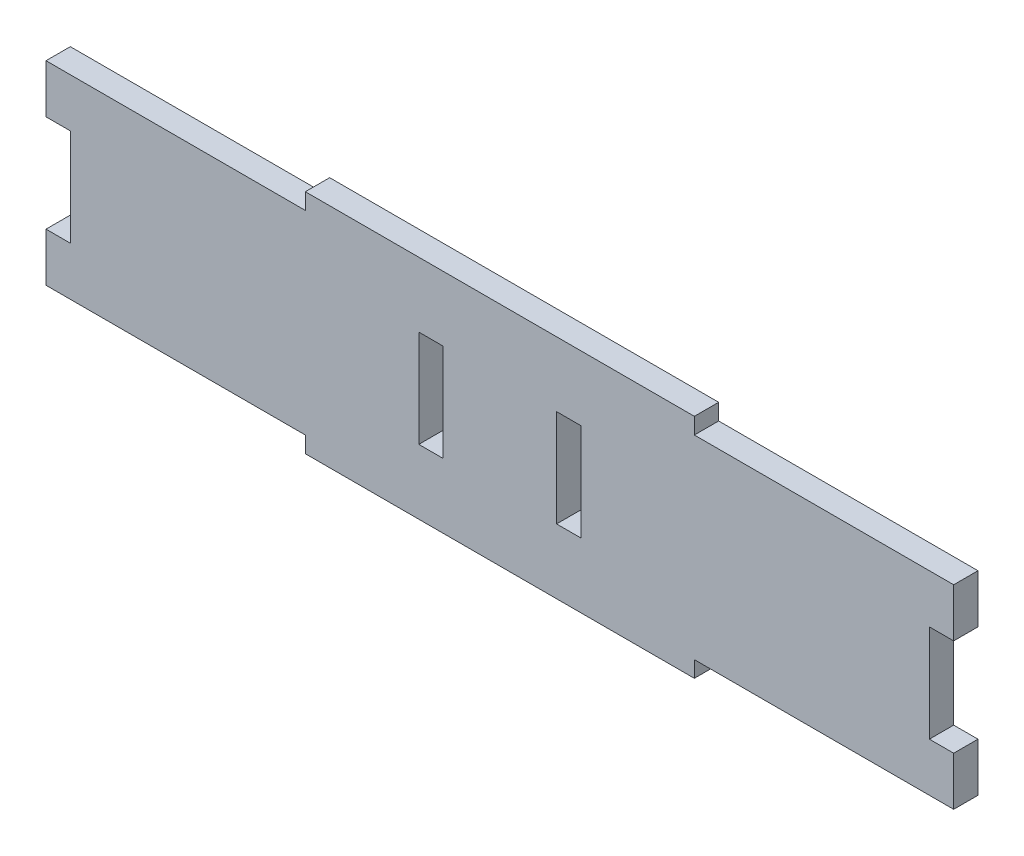
SolidWorks part; units mm, degrees
material "2024 Alloy"
ref_plane "Front" through (0, 0, 0) normal (0, 0, 1) x (1, 0, 0)
ref_plane "Top" through (0, 0, 0) normal (0, 1, 0) x (1, 0, 0)
ref_plane "Right" through (0, 0, 0) normal (1, 0, 0) x (0, 0, -1)
sketch "Sketch1" plane through (0, 0, 0) normal (0, 0, 1) x (1, 0, 0)
  line L0 (-177.8, 0) -> (177.8, 0) construction
  line L1 (-177.8, -44.45) -> (177.8, -44.45)
  line L2 (-177.8, -44.45) -> (-177.8, 44.45)
  line L4 (177.8, -44.45) -> (177.8, 44.45)
  line L5 (-177.8, -44.45) -> (177.8, 44.45) construction
  line L6 (-177.8, 44.45) -> (177.8, -44.45) construction
  line L11 (0, 44.45) -> (0, -44.45) construction
  line L16 (152.4, 50.8) -> (130.175, 50.8)
  line L17 (-177.8, 44.45) -> (177.8, 44.45)
  line L18 (-76.2, -44.45) -> (-76.2, -38.1)
  line L19 (76.2, 38.1) -> (76.2, 44.45)
  line L20 (76.2, -38.1) -> (76.2, -44.45)
  line L27 (-177.8, 19.05) -> (-177.8, -19.05)
  line L28 (177.8, 19.05) -> (177.8, -19.05)
  line L29 (-76.2, -38.1) -> (-177.8, -38.1)
  line L30 (76.2, -38.1) -> (177.8, -38.1)
  line L31 (76.2, 38.1) -> (177.8, 38.1)
  line L32 (-76.2, 44.45) -> (-76.2, 38.1)
  line L33 (-76.2, 38.1) -> (-177.8, 38.1)
  line L34 (-177.8, 19.05) -> (-168.275, 19.05)
  line L36 (-168.275, -19.05) -> (-177.8, -19.05)
  line L37 (-168.275, -19.05) -> (-168.275, 19.05)
  line L38 (168.275, -19.05) -> (168.275, 19.05)
  line L39 (177.8, 19.05) -> (168.275, 19.05)
  line L40 (177.8, 19.05) -> (177.8, -19.05)
  line L41 (168.275, -19.05) -> (177.8, -19.05)
  point P0 (0, 0)
  point P33 (-168.275, 0)
  dimension "D1" = 88.9
  dimension "D2" = 355.6
  dimension "D3" = 101.6
  dimension "D4" = 101.6
  dimension "D5" = 6.35
  dimension "D6" = 9.525
  dimension "D7" = 19.05
extrude "Boss-Extrude1" add sketch "Sketch1" along normal blind 9.525
sketch "Sketch2" plane through (0, 0, 9.525) normal (0, 0, 1) x (1, 0, 0)
  line L0 (-31.75, 19.05) -> (-31.75, -19.05)
  line L1 (-31.75, -19.05) -> (-22.225, -19.05)
  line L2 (-22.225, -19.05) -> (-22.225, 19.05)
  line L3 (-22.225, 19.05) -> (-31.75, 19.05)
  line L4 (-76.2, -44.45) -> (76.2, -44.45) construction
  line L5 (0, -44.45) -> (0, 44.45) construction
  line L6 (-76.2, 44.45) -> (76.2, 44.45) construction
  line L7 (22.225, -19.05) -> (22.225, 19.05)
  line L8 (31.75, -19.05) -> (22.225, -19.05)
  line L9 (31.75, 19.05) -> (31.75, -19.05)
  line L10 (22.225, 19.05) -> (31.75, 19.05)
  line L11 (-76.2, 38.1) -> (-177.8, 38.1) construction
  dimension "D1" = 53.975
  dimension "D2" = 38.1
  dimension "D3" = 9.525
  dimension "D4" = 19.05
extrude "Cut-Extrude1" cut sketch "Sketch2" against normal through all
